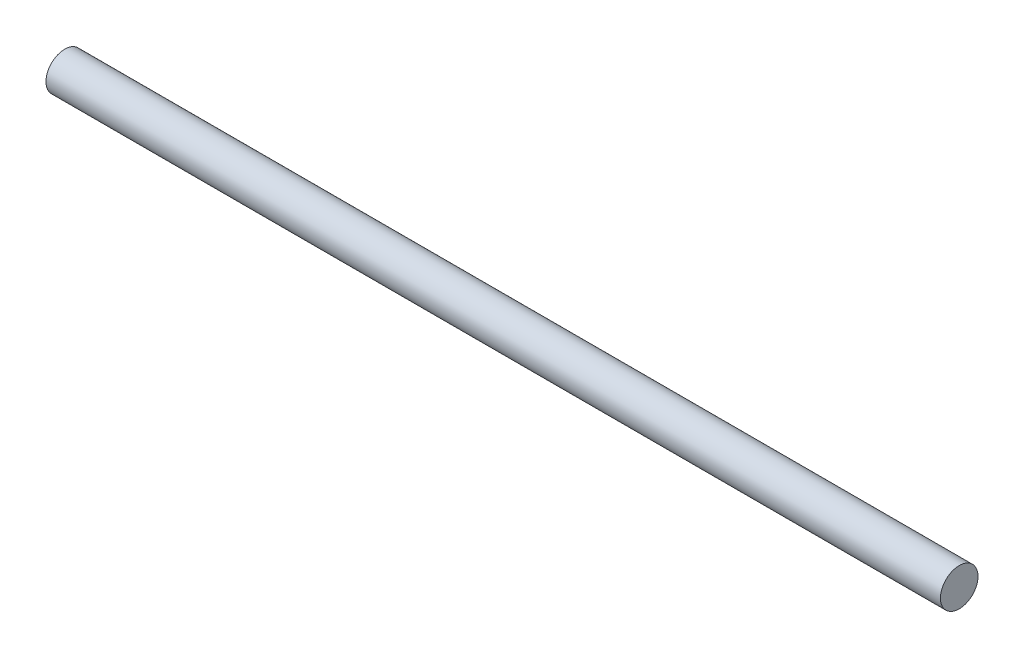
SolidWorks part; units mm, degrees
ref_plane "Front Plane" through (0, 0, 0) normal (0, 0, 1) x (1, 0, 0)
ref_plane "Top Plane" through (0, 0, 0) normal (0, 1, 0) x (1, 0, 0)
ref_plane "Right Plane" through (0, 0, 0) normal (1, 0, 0) x (0, 0, -1)
sketch "Sketch1" plane through (0, 0, 0) normal (1, 0, 0) x (0, 0, -1)
  circle A0 centre (0, 0) radius 2.667
  point P3 (0, 0)
  dimension "D1" = 5.334
extrude "Boss-Extrude1" add sketch "Sketch1" along normal blind 127
